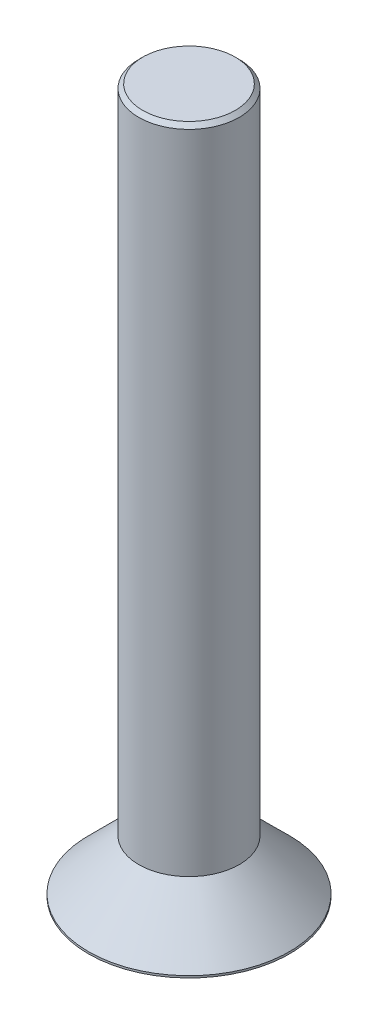
SolidWorks part; units mm, degrees
ref_plane "前视基准面" through (0, 0, 0) normal (0, 0, 1) x (1, 0, 0)
ref_plane "上视基准面" through (0, 0, 0) normal (0, 1, 0) x (1, 0, 0)
ref_plane "右视基准面" through (0, 0, 0) normal (1, 0, 0) x (0, 0, -1)
sketch "草图1" plane through (0, 0, 0) normal (0, 1, 0) x (1, 0, 0)
  circle A0 centre (0, 0) radius 5
  dimension "D1" = 10
extrude "凸台-拉伸1" add sketch "草图1" along normal blind 2.6
chamfer "倒角1" distance 2.5 angle 45 1 edges at (0, 2.6, 5)
sketch "草图2" plane through (0, 0, 0) normal (0, -1, 0) x (1, 0, 0)
  line L1 (1.54, -0.8891) -> (1.54, 0.8891)
  line L2 (1.54, 0.8891) -> (0, 1.7782)
  line L3 (0, 1.7782) -> (-1.54, 0.8891)
  line L4 (-1.54, 0.8891) -> (-1.54, -0.8891)
  line L5 (-1.54, -0.8891) -> (0, -1.7782)
  line L6 (0, -1.7782) -> (1.54, -0.8891)
  circle A0 centre (0, 0) radius 1.54 construction
  dimension "D1" = 3.08
extrude "切除-拉伸1" cut sketch "草图2" against normal blind 0.95
sketch "草图3" plane through (0, 2.6, 0) normal (0, 1, 0) x (1, 0, 0)
  circle A0 centre (0, 0) radius 2.5
  dimension "D1" = 5
extrude "凸台-拉伸2" add sketch "草图3" along normal blind 32.4
chamfer "倒角2" distance 0.2 angle 45 1 edges at (0, 35, 2.5)
